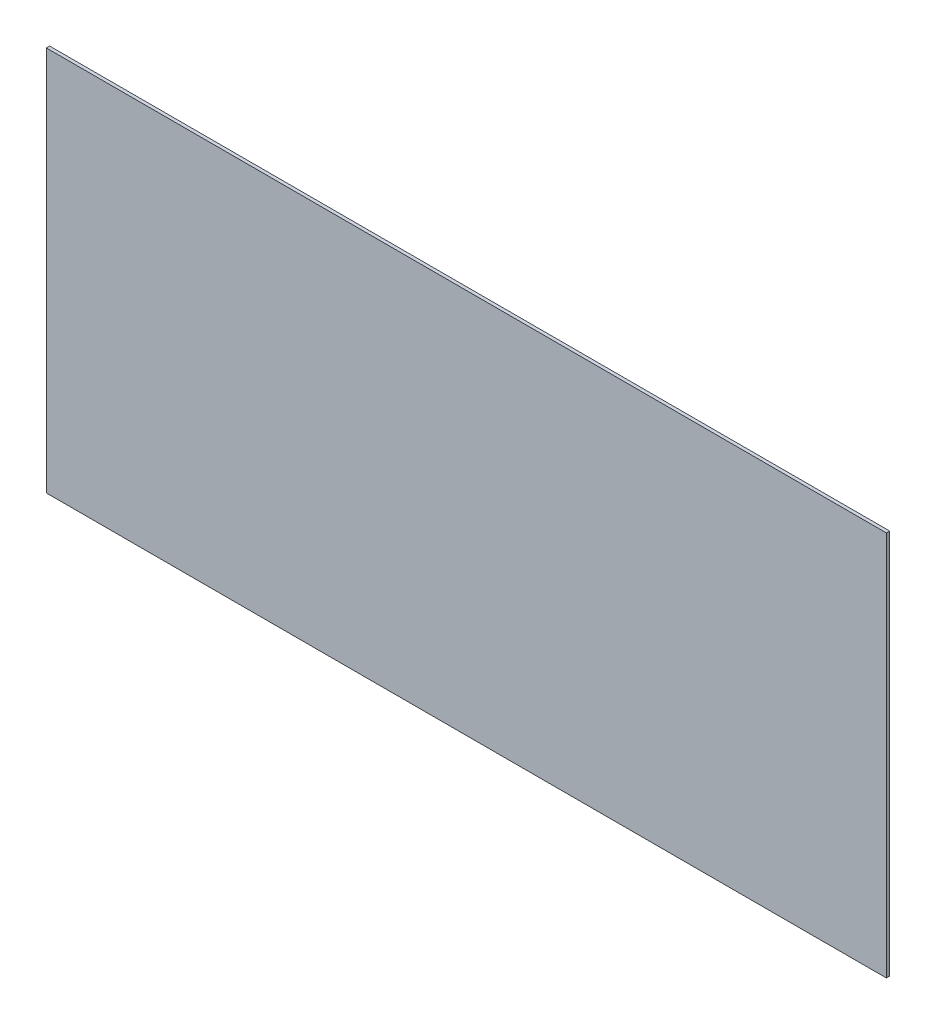
SolidWorks part; units mm, degrees
ref_plane "前视基准面" through (0, 0, 0) normal (0, 0, 1) x (1, 0, 0)
ref_plane "上视基准面" through (0, 0, 0) normal (0, 1, 0) x (1, 0, 0)
ref_plane "右视基准面" through (0, 0, 0) normal (1, 0, 0) x (0, 0, -1)
other "Configuration Table"
sketch "草图3" plane through (0, 0, 0) normal (0, 0, 1) x (1, 0, 0)
  line L0 (661.6078, 901.696) -> (1681.6078, 901.696)
  line L1 (661.6078, 901.696) -> (661.6078, 433.696)
  line L2 (661.6078, 433.696) -> (1681.6078, 433.696)
  line L3 (1681.6078, 433.696) -> (1681.6078, 901.696)
extrude "凸台-拉伸1" add sketch "草图3" along normal blind 4
